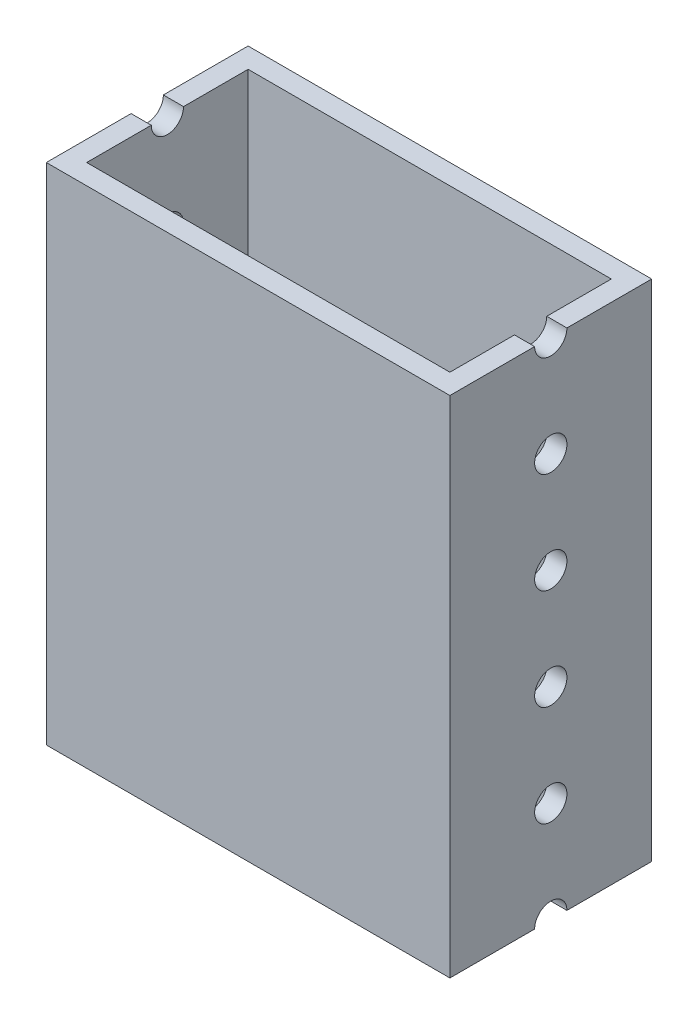
SolidWorks part; units mm, degrees
ref_plane "Front Plane" through (0, 0, 0) normal (0, 0, 1) x (1, 0, 0)
ref_plane "Top Plane" through (0, 0, 0) normal (0, 1, 0) x (1, 0, 0)
ref_plane "Right Plane" through (0, 0, 0) normal (1, 0, 0) x (0, 0, -1)
sketch "Sketch2" plane through (0, 0, 0) normal (0, 1, 0) x (1, 0, 0)
  line L0 (-22.86, 10.16) -> (22.86, 10.16)
  line L1 (-25.4, -12.7) -> (25.4, -12.7)
  line L2 (-25.4, -12.7) -> (-25.4, 12.7)
  line L3 (-25.4, 12.7) -> (25.4, 12.7)
  line L4 (25.4, -12.7) -> (25.4, 12.7)
  line L5 (-25.4, -12.7) -> (25.4, 12.7) construction
  line L6 (-25.4, 12.7) -> (25.4, -12.7) construction
  line L7 (22.86, -10.16) -> (22.86, 10.16)
  line L8 (-22.86, -10.16) -> (22.86, -10.16)
  line L9 (-22.86, -10.16) -> (-22.86, 10.16)
  point P0 (0, 0)
  dimension "D1" = 50.8
  dimension "D2" = 25.4
  dimension "D3" = 2.54
extrude "Boss-Extrude1" add sketch "Sketch2" along normal blind 635
sketch "Sketch3" plane through (25.4, 0, 0) normal (1, 0, 0) x (0, 0, -1)
  line L0 (-12.7, 0) -> (12.7, 0) construction
  circle A0 centre (0, 0) radius 2.032
  circle A1 centre (0, 12.7) radius 2.032
  circle A2 centre (0, 25.4) radius 2.032
  circle A3 centre (0, 38.1) radius 2.032
  circle A4 centre (0, 50.8) radius 2.032
  circle A5 centre (0, 63.5) radius 2.032
  circle A6 centre (0, 76.2) radius 2.032
  circle A7 centre (0, 88.9) radius 2.032
  circle A8 centre (0, 101.6) radius 2.032
  circle A9 centre (0, 114.3) radius 2.032
  circle A10 centre (0, 127) radius 2.032
  circle A11 centre (0, 139.7) radius 2.032
  circle A12 centre (0, 152.4) radius 2.032
  circle A13 centre (0, 165.1) radius 2.032
  circle A14 centre (0, 177.8) radius 2.032
  circle A15 centre (0, 190.5) radius 2.032
  circle A16 centre (0, 203.2) radius 2.032
  circle A17 centre (0, 215.9) radius 2.032
  circle A18 centre (0, 228.6) radius 2.032
  circle A19 centre (0, 241.3) radius 2.032
  circle A20 centre (0, 254) radius 2.032
  circle A21 centre (0, 266.7) radius 2.032
  circle A22 centre (0, 279.4) radius 2.032
  circle A23 centre (0, 292.1) radius 2.032
  circle A24 centre (0, 304.8) radius 2.032
  circle A25 centre (0, 317.5) radius 2.032
  circle A26 centre (0, 330.2) radius 2.032
  circle A27 centre (0, 342.9) radius 2.032
  circle A28 centre (0, 355.6) radius 2.032
  circle A29 centre (0, 368.3) radius 2.032
  circle A30 centre (0, 381) radius 2.032
  circle A31 centre (0, 393.7) radius 2.032
  circle A32 centre (0, 406.4) radius 2.032
  circle A33 centre (0, 419.1) radius 2.032
  circle A34 centre (0, 431.8) radius 2.032
  circle A35 centre (0, 444.5) radius 2.032
  circle A36 centre (0, 457.2) radius 2.032
  circle A37 centre (0, 469.9) radius 2.032
  circle A38 centre (0, 482.6) radius 2.032
  circle A39 centre (0, 495.3) radius 2.032
  circle A40 centre (0, 508) radius 2.032
  circle A41 centre (0, 520.7) radius 2.032
  circle A42 centre (0, 533.4) radius 2.032
  circle A43 centre (0, 546.1) radius 2.032
  circle A44 centre (0, 558.8) radius 2.032
  circle A45 centre (0, 571.5) radius 2.032
  circle A46 centre (0, 584.2) radius 2.032
  circle A47 centre (0, 596.9) radius 2.032
  circle A48 centre (0, 609.6) radius 2.032
  circle A49 centre (0, 622.3) radius 2.032
  dimension "D1" = 4.064
  dimension "D2" = 50
extrude "Cut-Extrude1" cut sketch "Sketch3" against normal through all
sketch "Sketch6" plane through (0, 635, 0) normal (0, 1, 0) x (1, 0, 0)
  line L4 (25.4, -12.7) -> (25.4, 12.7)
  line L5 (25.4, 12.7) -> (-25.4, 12.7)
  line L6 (-25.4, 12.7) -> (-25.4, -12.7)
  line L7 (-25.4, -12.7) -> (25.4, -12.7)
  line L8 (25.4, -12.7) -> (25.4, 12.7)
  line L9 (25.4, 12.7) -> (-25.4, 12.7)
  line L10 (-25.4, 12.7) -> (-25.4, -12.7)
  line L11 (-25.4, -12.7) -> (25.4, -12.7)
  dimension "D1" = 0
extrude "Cut-Extrude4" cut sketch "Sketch6" against normal blind 571.5
